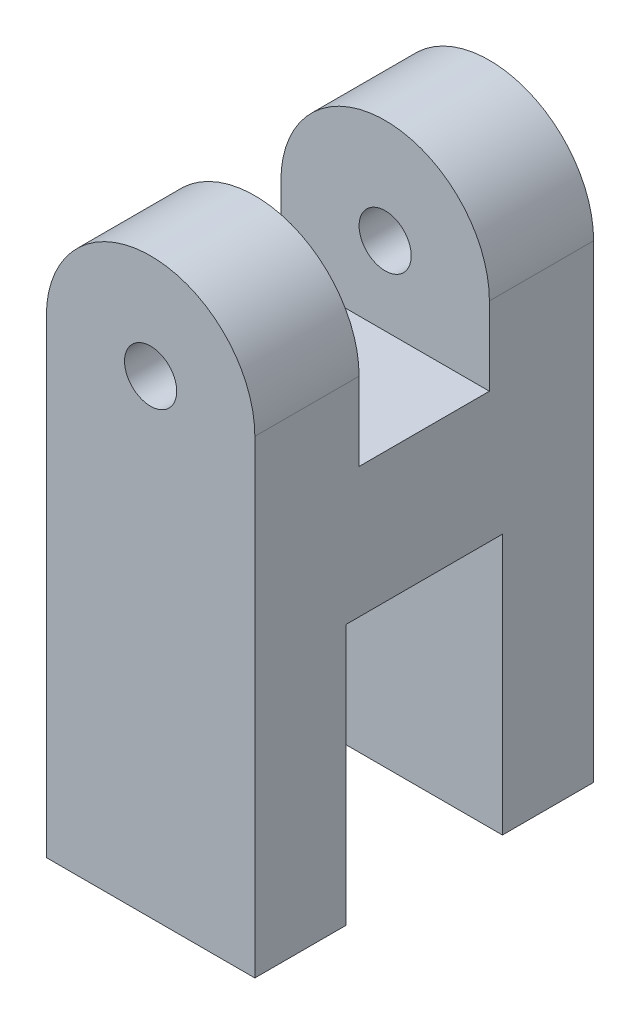
SolidWorks part; units mm, degrees
ref_plane "Front Plane" through (0, 0, 0) normal (0, 0, 1) x (1, 0, 0)
ref_plane "Top Plane" through (0, 0, 0) normal (0, 1, 0) x (1, 0, 0)
ref_plane "Right Plane" through (0, 0, 0) normal (1, 0, 0) x (0, 0, -1)
sketch "Sketch1" plane through (0, 0, 0) normal (0, 1, 0) x (1, 0, 0)
  line L0 (-4, -6.5) -> (4, -6.5)
  line L1 (-4, -6.5) -> (-4, 6.5)
  line L2 (4, -6.5) -> (4, 6.5)
  line L3 (-4, 6.5) -> (4, 6.5)
  line L4 (-4, -6.5) -> (4, 6.5) construction
  line L5 (4, -6.5) -> (-4, 6.5) construction
  point P1 (0, 0)
  dimension "D1" = 13
  dimension "D2" = 8
extrude "Boss-Extrude1" add sketch "Sketch1" along normal blind 12
sketch "Sketch2" plane through (0, 12, 0) normal (0, 1, 0) x (1, 0, 0)
  line L0 (-6.5, -2.5) -> (6.5, -2.5)
  line L1 (-6.5, -2.5) -> (-6.5, 2.5)
  line L2 (6.5, -2.5) -> (6.5, 2.5)
  line L3 (-6.5, 2.5) -> (6.5, 2.5)
  line L4 (-6.5, -2.5) -> (6.5, 2.5) construction
  line L5 (6.5, -2.5) -> (-6.5, 2.5) construction
  point P1 (0, 0)
  dimension "D1" = 5
  dimension "D2" = 13
extrude "Cut-Extrude1" cut sketch "Sketch2" against normal blind 7
sketch "Sketch3" plane through (0, 0, -6.5) normal (0, 0, -1) x (-1, 0, 0)
  line L0 (-4, 12) -> (4, 12) construction
  line L1 (-4, 12) -> (-4, 0) construction
  circle A0 centre (0, 8) radius 1
  point P4 (0, 12)
  point P5 (0, 0)
  dimension "D2" = 2
  dimension "D1" = 4
  dimension "D3" = 4
extrude "Cut-Extrude2" cut sketch "Sketch3" against normal through all
sketch "Sketch4" plane through (0, 0, -6.5) normal (0, 0, -1) x (-1, 0, 0)
  line L0 (-4, 12) -> (-4, 0) construction
  line L1 (-4, 12) -> (4, 12) construction
  arc A0 (-4, 8) -> (0, 12) centre (0, 8) cw
  dimension "D1" = 4
extrude "Cut-Extrude3" cut sketch "Sketch4" against normal blind 13 and the other way through all
mirror "Mirror1" about plane through (0, 0, 0) normal (1, 0, 0) of "Cut-Extrude3"
sketch "Sketch7" plane through (0, 0, 0) normal (0, -1, 0) x (1, 0, 0)
  line L0 (-4, -6.5) -> (-4, 6.5) construction
  line L1 (4, -6.5) -> (-4, -6.5)
  line L2 (4, -6.5) -> (4, -3)
  line L3 (4, -3) -> (-4, -3)
  line L4 (-4, -6.5) -> (-4, -3)
  dimension "D1" = 3.5
extrude "Boss-Extrude4" add sketch "Sketch7" along normal blind 10
mirror "Mirror2" about plane through (0, 0, 0) normal (0, 0, 1) of "Boss-Extrude4"
